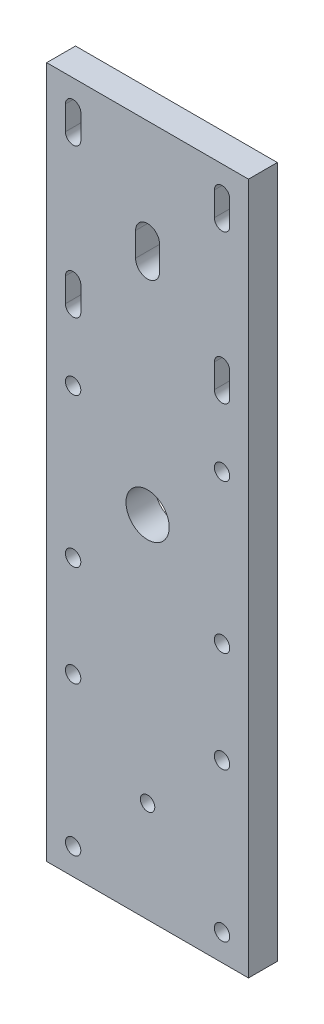
SolidWorks part; units mm, degrees
ref_plane "前视基准面" through (0, 0, 0) normal (0, 0, 1) x (1, 0, 0)
ref_plane "上视基准面" through (0, 0, 0) normal (0, 1, 0) x (1, 0, 0)
ref_plane "右视基准面" through (0, 0, 0) normal (1, 0, 0) x (0, 0, -1)
sketch "草图1" plane through (0, 0, 0) normal (0, 0, 1) x (1, 0, 0)
  line L0 (-21, 42) -> (21, 0) construction
  line L1 (-21, 87) -> (21, 87)
  line L2 (-21, 87) -> (-21, 0)
  line L3 (-21, 0) -> (21, 0)
  line L4 (21, 87) -> (21, 0)
  line L9 (-21, 42) -> (21, 42)
  line L10 (-21, 42) -> (-21, 0)
  line L11 (-21, 0) -> (21, 0)
  line L12 (21, 42) -> (21, 0)
  line L13 (21, 42) -> (-21, 0) construction
  line L14 (-21, 87) -> (21, 45)
  line L15 (-21, 87) -> (21, 87)
  line L16 (-21, 87) -> (-21, 45)
  line L17 (-21, 45) -> (21, 45)
  line L18 (21, 87) -> (21, 45)
  line L23 (21, 87) -> (-21, 45) construction
  line L24 (-21, -10) -> (21, -52)
  line L29 (-21, 0) -> (21, 0)
  line L30 (-21, 0) -> (-21, -10)
  line L31 (-21, -10) -> (21, -10)
  line L32 (21, 0) -> (21, -10)
  line L33 (-21, -10) -> (21, -10)
  line L34 (-21, -10) -> (-21, -52)
  line L35 (-21, -52) -> (21, -52)
  line L36 (21, -10) -> (21, -52)
  line L37 (21, -10) -> (-21, -52)
  line L38 (-21, 92) -> (21, 50)
  line L39 (-21, 92) -> (21, 92)
  line L40 (-21, 92) -> (-21, 50)
  line L41 (-21, 50) -> (21, 50)
  line L42 (21, 92) -> (21, 50)
  line L43 (21, 92) -> (-21, 50) construction
  line L44 (-15.5, 86.5) -> (-15.5, 81.5) construction
  line L45 (-13.9, 86.5) -> (-13.9, 81.5)
  line L46 (-17.1, 86.5) -> (-17.1, 81.5)
  line L47 (15.5, 86.5) -> (15.5, 81.5) construction
  line L48 (17.1, 86.5) -> (17.1, 81.5)
  line L49 (13.9, 86.5) -> (13.9, 81.5)
  line L50 (-15.5, 55.5) -> (-15.5, 50.5) construction
  line L51 (-13.9, 55.5) -> (-13.9, 50.5)
  line L52 (-17.1, 55.5) -> (-17.1, 50.5)
  line L53 (15.5, 55.5) -> (15.5, 50.5) construction
  line L54 (17.1, 55.5) -> (17.1, 50.5)
  line L55 (13.9, 55.5) -> (13.9, 50.5)
  line L56 (0, 71) -> (0, 66) construction
  line L57 (2.5, 71) -> (2.5, 66)
  line L58 (-2.5, 71) -> (-2.5, 66)
  circle A13 centre (0, 21) radius 4.5
  circle A15 centre (-15.5, -15.5) radius 1.6
  circle A16 centre (15.5, -15.5) radius 1.6
  circle A17 centre (-15.5, -46.5) radius 1.6
  circle A18 centre (15.5, -46.5) radius 1.6
  circle A19 centre (0, -31) radius 1.5
  arc A22 (-13.9, 86.5) -> (-17.1, 86.5) centre (-15.5, 86.5) ccw
  arc A23 (-17.1, 81.5) -> (-13.9, 81.5) centre (-15.5, 81.5) ccw
  arc A24 (17.1, 86.5) -> (13.9, 86.5) centre (15.5, 86.5) ccw
  arc A25 (13.9, 81.5) -> (17.1, 81.5) centre (15.5, 81.5) ccw
  arc A26 (-13.9, 55.5) -> (-17.1, 55.5) centre (-15.5, 55.5) ccw
  arc A27 (-17.1, 50.5) -> (-13.9, 50.5) centre (-15.5, 50.5) ccw
  arc A28 (17.1, 55.5) -> (13.9, 55.5) centre (15.5, 55.5) ccw
  arc A29 (13.9, 50.5) -> (17.1, 50.5) centre (15.5, 50.5) ccw
  arc A30 (2.5, 71) -> (-2.5, 71) centre (0, 71) ccw
  arc A31 (-2.5, 66) -> (2.5, 66) centre (0, 66) ccw
  circle A32 centre (-15.5, 36.5) radius 1.6
  circle A33 centre (15.5, 36.5) radius 1.6
  circle A34 centre (15.5, 5.5) radius 1.6
  circle A35 centre (-15.5, 5.5) radius 1.6
  point P6 (0, 0)
  point P18 (15.5, 81.5)
  point P19 (-15.5, 50.5)
  point P20 (15.5, 50.5)
  point P21 (-15.5, 81.5)
  point P22 (-15.5, 84)
  point P41 (15.5, 84)
  point P51 (-15.5, 86.5)
  point P54 (15.5, 86.5)
  point P55 (-15.5, 55.5)
  point P56 (15.5, 55.5)
  point P57 (0, 66)
  point P58 (0, 71)
  point P67 (-15.5, 53)
  point P74 (15.5, 53)
  point P81 (0, 68.5)
  dimension "D9" = 50
  dimension "D10" = 10
  dimension "D12" = 9
  dimension "D13" = 3.2
  dimension "D11" = 3.2
  dimension "D16" = 3
  dimension "D20" = 3.2
  dimension "D1" = 42
  dimension "D2" = 42
  dimension "D3" = 42
  dimension "D4" = 42
  dimension "D5" = 42
  dimension "D6" = 31
  dimension "D7" = 42
  dimension "D8" = 45
  dimension "D14" = 31
  dimension "D15" = 42
  dimension "D17" = 42
  dimension "D18" = 31
  dimension "D19" = 31
  dimension "D21" = 5
extrude "凸台-拉伸1" add sketch "草图1" along normal blind 6
